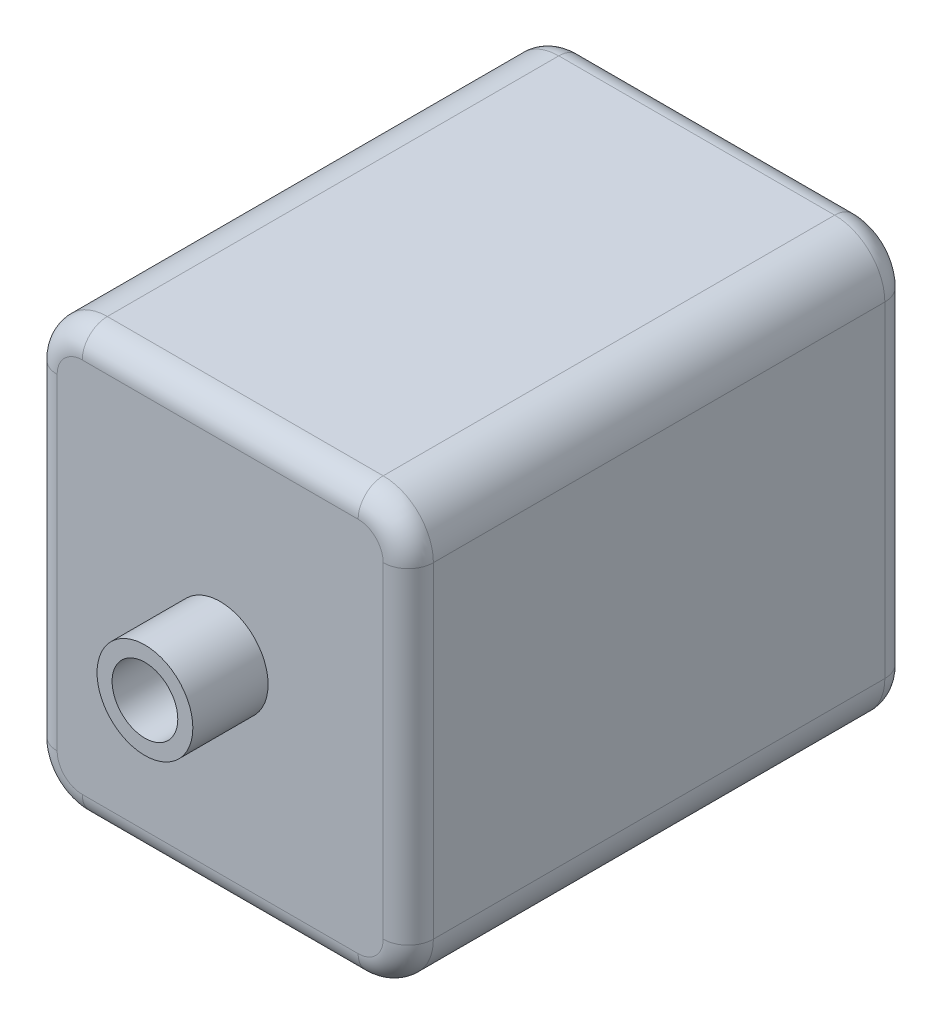
SolidWorks part; units mm, degrees
ref_plane "Front Plane" through (0, 0, 0) normal (0, 0, 1) x (1, 0, 0)
ref_plane "Top Plane" through (0, 0, 0) normal (0, 1, 0) x (1, 0, 0)
ref_plane "Right Plane" through (0, 0, 0) normal (1, 0, 0) x (0, 0, -1)
sketch "Sketch1" plane through (0, 0, 0) normal (0, 0, 1) x (1, 0, 0)
  line L0 (-20, -44.9927) -> (35, -44.9927)
  line L1 (-20, -46.9927) -> (35, -46.9927)
  line L2 (-30, -36.9927) -> (-30, 28.0073)
  line L11 (-20, 38.0073) -> (35, 38.0073)
  line L12 (45, -36.9927) -> (45, 28.0073)
  line L13 (19.754, -26.9927) -> (-20.246, -26.9927) construction
  line L18 (-25.5107, -46.9927) -> (-30, -46.9927) construction
  line L20 (-30, -46.9927) -> (-30, -39.3247) construction
  line L22 (43, -36.9927) -> (43, 28.0073)
  line L23 (-20, 36.0073) -> (35, 36.0073)
  line L24 (-28, -36.9927) -> (-28, 28.0073)
  arc A0 (35, -46.9927) -> (45, -36.9927) centre (35, -36.9927) ccw
  arc A1 (35, 38.0073) -> (45, 28.0073) centre (35, 28.0073) cw
  arc A2 (-30, 28.0073) -> (-20, 38.0073) centre (-20, 28.0073) cw
  arc A3 (-20, -46.9927) -> (-30, -36.9927) centre (-20, -36.9927) cw
  arc A4 (35, -44.9927) -> (43, -36.9927) centre (35, -36.9927) ccw
  arc A5 (35, 36.0073) -> (43, 28.0073) centre (35, 28.0073) cw
  arc A6 (-28, 28.0073) -> (-20, 36.0073) centre (-20, 28.0073) cw
  arc A7 (-20, -44.9927) -> (-28, -36.9927) centre (-20, -36.9927) cw
  point P2 (45, -46.9927)
  point P9 (45, 38.0073)
  point P23 (-30, -46.9927)
  dimension "D4" = 10
  dimension "D1" = 85
  dimension "D2" = 20
  dimension "D3" = 75
  dimension "D5" = 2
extrude "Boss-Extrude1" add sketch "Sketch1" along normal blind 100
sketch "Sketch2" plane through (0, 0, 0) normal (0, 0, -1) x (-1, 0, 0)
  line L4 (-35, -46.9927) -> (20, -46.9927)
  line L5 (30, -36.9927) -> (30, 28.0073)
  line L6 (20, 38.0073) -> (-35, 38.0073)
  line L7 (-45, 28.0073) -> (-45, -36.9927)
  line L8 (-35, -46.9927) -> (20, -46.9927)
  line L9 (30, -36.9927) -> (30, 28.0073)
  line L10 (20, 38.0073) -> (-35, 38.0073)
  line L11 (-45, 28.0073) -> (-45, -36.9927)
  arc A4 (-45, -36.9927) -> (-35, -46.9927) centre (-35, -36.9927) ccw
  arc A5 (20, -46.9927) -> (30, -36.9927) centre (20, -36.9927) ccw
  arc A6 (30, 28.0073) -> (20, 38.0073) centre (20, 28.0073) ccw
  arc A7 (-35, 38.0073) -> (-45, 28.0073) centre (-35, 28.0073) ccw
  arc A8 (-45, -36.9927) -> (-35, -46.9927) centre (-35, -36.9927) ccw
  arc A9 (20, -46.9927) -> (30, -36.9927) centre (20, -36.9927) ccw
  arc A10 (30, 28.0073) -> (20, 38.0073) centre (20, 28.0073) ccw
  arc A11 (-35, 38.0073) -> (-45, 28.0073) centre (-35, 28.0073) ccw
  dimension "D1" = 0
extrude "Boss-Extrude2" add sketch "Sketch2" against normal blind 3
sketch "Sketch4" plane through (0, 0, 100) normal (0, 0, 1) x (1, 0, 0)
  line L4 (-20, -46.9927) -> (35, -46.9927)
  line L5 (-30, 28.0073) -> (-30, -36.9927)
  line L6 (35, 38.0073) -> (-20, 38.0073)
  line L7 (45, -36.9927) -> (45, 28.0073)
  line L8 (-20, -46.9927) -> (35, -46.9927)
  line L9 (-30, 28.0073) -> (-30, -36.9927)
  line L10 (35, 38.0073) -> (-20, 38.0073)
  line L11 (45, -36.9927) -> (45, 28.0073)
  arc A4 (35, -46.9927) -> (45, -36.9927) centre (35, -36.9927) ccw
  arc A5 (-30, -36.9927) -> (-20, -46.9927) centre (-20, -36.9927) ccw
  arc A6 (-20, 38.0073) -> (-30, 28.0073) centre (-20, 28.0073) ccw
  arc A7 (45, 28.0073) -> (35, 38.0073) centre (35, 28.0073) ccw
  arc A8 (35, -46.9927) -> (45, -36.9927) centre (35, -36.9927) ccw
  arc A9 (-30, -36.9927) -> (-20, -46.9927) centre (-20, -36.9927) ccw
  arc A10 (-20, 38.0073) -> (-30, 28.0073) centre (-20, 28.0073) ccw
  arc A11 (45, 28.0073) -> (35, 38.0073) centre (35, 28.0073) ccw
  dimension "D1" = 0
extrude "Boss-Extrude3" add sketch "Sketch4" against normal blind 2
fillet "Fillet2" radius 5 32 edges at (40.6569, 33.6641, 98) (43, -4.4927, 98) (40.6569, -42.6496, 98) (7.5, -44.9927, 98) (-25.6569, -42.6496, 98) (-28, -4.4927, 98) (-25.6569, 33.6641, 98) (-25.6569, 33.6641, 3) (-28, -4.4927, 3) (-25.6569, -42.6496, 3) (7.5, -44.9927, 3) (40.6569, -42.6496, 3) (43, -4.4927, 3) (40.6569, 33.6641, 3) (-27.0711, -44.0638, 0) (-30, -4.4927, 0) (-27.0711, 35.0784, 0) (7.5, 38.0073, 0) (42.0711, 35.0784, 0) (45, -4.4927, 0) (42.0711, -44.0638, 0) (-27.0711, -44.0638, 100) (-30, -4.4927, 100) (-27.0711, 35.0784, 100) (7.5, 38.0073, 100) (42.0711, 35.0784, 100) (45, -4.4927, 100) (42.0711, -44.0638, 100) (7.5, 36.0073, 98) (7.5, 36.0073, 3) (7.5, -46.9927, 0) (7.5, -46.9927, 100)
sketch "Sketch5" plane through (0, 0, 100) normal (0, 0, 1) x (1, 0, 0)
  circle A0 centre (7.5, -4.4927) radius 6.55
  circle A1 centre (7.5, -4.4927) radius 9.55
extrude "Boss-Extrude4" add sketch "Sketch5" along normal blind 15
